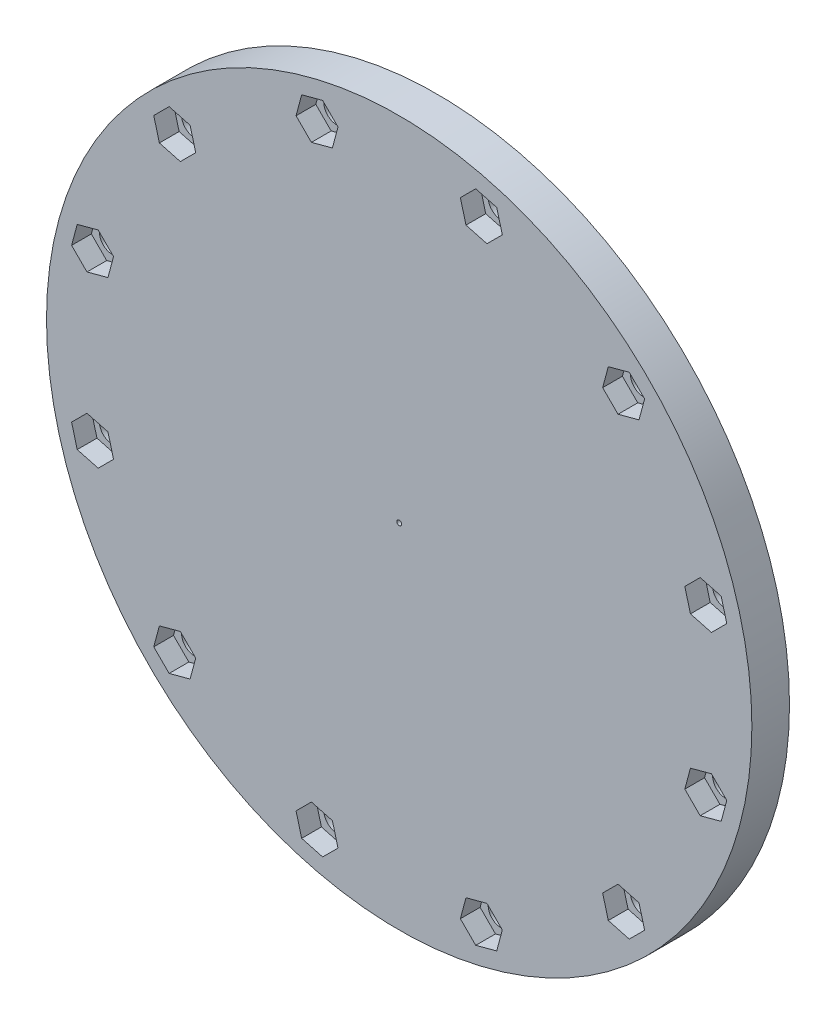
SolidWorks part; units mm, degrees
ref_plane "Front" through (0, 0, 0) normal (0, 0, 1) x (1, 0, 0)
ref_plane "Top" through (0, 0, 0) normal (0, 1, 0) x (1, 0, 0)
ref_plane "Right" through (0, 0, 0) normal (1, 0, 0) x (0, 0, -1)
sketch "Sketch1" plane through (0, 0, 0) normal (0, 0, 1) x (1, 0, 0)
  circle A0 centre (0, 0) radius 75
  dimension "D1" = 150
extrude "Boss-Extrude1" add sketch "Sketch1" along normal blind 8
hole_wizard "M5 Clearance Hole1" positions "Sketch3" profile "Sketch5" hole size "M5" standard "ANSI Metric" end condition up to next
sketch "Sketch3" plane through (0, 0, 0) normal (0, 0, -1) x (-1, 0, 0)
  line L14 (0, 0) -> (0, -75) construction
  line L15 (17.4703, -65.2) -> (-17.4703, 65.2) construction
  line L17 (65.2, 17.4703) -> (-65.2, -17.4703) construction
  line L19 (47.7297, 47.7297) -> (-47.7297, -47.7297) construction
  line L21 (0, 0) -> (17.4703, -65.2) construction
  line L23 (-17.4703, -65.2) -> (17.4703, 65.2) construction
  line L24 (-65.2, 17.4703) -> (65.2, -17.4703) construction
  line L26 (-47.7297, 47.7297) -> (47.7297, -47.7297) construction
  circle A1 centre (0, 0) radius 75 construction
  circle A3 centre (0, 0) radius 67.5 construction
  point P5 (-47.7297, 47.7297)
  point P11 (65.2, -17.4703)
  point P13 (47.7297, -47.7297)
  point P21 (-65.2, 17.4703)
  point P62 (-17.4703, 65.2)
  point P64 (-65.2, -17.4703)
  point P66 (-47.7297, -47.7297)
  point P68 (17.4703, -65.2)
  point P70 (17.4703, -65.2)
  point P72 (65.2, 17.4703)
  point P74 (47.7297, 47.7297)
  point P450 (17.4703, 65.2)
  point P453 (-17.4703, -65.2)
  dimension "D1" = 30
  dimension "D2" = 135
  dimension "D3" = 30
  dimension "D4" = 15
  dimension "D5" = 30
  dimension "D6" = 30
  dimension "D7" = 30
sketch "Sketch5" plane through (17.4703, -65.2, 0) normal (1, 0, 0) x (0, 1, 0)
  line L0 (0, 0) -> (0, 8)
  line L1 (0, 8) -> (2.75, 8)
  line L2 (2.75, 8) -> (2.75, 0)
  line L5 (2.75, 0) -> (0, 0)
  line L11 (0, -6.35) -> (0, 107.95) construction
  dimension "Thru Hole Dia." = 5.5
  dimension "Thru Hole Depth" = 8
sketch "Sketch6" plane through (0, 0, 8) normal (0, 0, -1) x (-1, 0, 0)
  line L0 (0, 0) -> (-47.7297, 47.7297) construction
  line L25 (-43.2683, 46.5343) -> (-44.4637, 50.9957)
  line L26 (-44.4637, 50.9957) -> (-48.9251, 52.1911)
  line L27 (-48.9251, 52.1911) -> (-52.1911, 48.9251)
  line L28 (-52.1911, 48.9251) -> (-50.9957, 44.4637)
  line L29 (-50.9957, 44.4637) -> (-46.5343, 43.2683)
  line L30 (-46.5343, 43.2683) -> (-43.2683, 46.5343)
  line L79 (-13.0089, 66.3954) -> (-16.2749, 69.6614)
  line L80 (-14.2043, 61.934) -> (-13.0089, 66.3954)
  line L81 (-18.6657, 60.7386) -> (-14.2043, 61.934)
  line L82 (-21.9317, 64.0046) -> (-18.6657, 60.7386)
  line L83 (-20.7363, 68.466) -> (-21.9317, 64.0046)
  line L84 (-16.2749, 69.6614) -> (-20.7363, 68.466)
  line L85 (21.9317, 64.0046) -> (20.7363, 68.466)
  line L86 (18.6657, 60.7386) -> (21.9317, 64.0046)
  line L87 (14.2043, 61.934) -> (18.6657, 60.7386)
  line L88 (13.0089, 66.3954) -> (14.2043, 61.934)
  line L89 (16.2749, 69.6614) -> (13.0089, 66.3954)
  line L90 (20.7363, 68.466) -> (16.2749, 69.6614)
  line L91 (50.9957, 44.4637) -> (52.1911, 48.9251)
  line L92 (46.5343, 43.2683) -> (50.9957, 44.4637)
  line L93 (43.2683, 46.5343) -> (46.5343, 43.2683)
  line L94 (44.4637, 50.9957) -> (43.2683, 46.5343)
  line L95 (48.9251, 52.1911) -> (44.4637, 50.9957)
  line L96 (52.1911, 48.9251) -> (48.9251, 52.1911)
  line L97 (66.3954, 13.0089) -> (69.6614, 16.2749)
  line L98 (61.934, 14.2043) -> (66.3954, 13.0089)
  line L99 (60.7386, 18.6657) -> (61.934, 14.2043)
  line L100 (64.0046, 21.9317) -> (60.7386, 18.6657)
  line L101 (68.466, 20.7363) -> (64.0046, 21.9317)
  line L102 (69.6614, 16.2749) -> (68.466, 20.7363)
  line L103 (64.0046, -21.9317) -> (68.466, -20.7363)
  line L104 (60.7386, -18.6657) -> (64.0046, -21.9317)
  line L105 (61.934, -14.2043) -> (60.7386, -18.6657)
  line L106 (66.3954, -13.0089) -> (61.934, -14.2043)
  line L107 (69.6614, -16.2749) -> (66.3954, -13.0089)
  line L108 (68.466, -20.7363) -> (69.6614, -16.2749)
  line L109 (44.4637, -50.9957) -> (48.9251, -52.1911)
  line L110 (43.2683, -46.5343) -> (44.4637, -50.9957)
  line L111 (46.5343, -43.2683) -> (43.2683, -46.5343)
  line L112 (50.9957, -44.4637) -> (46.5343, -43.2683)
  line L113 (52.1911, -48.9251) -> (50.9957, -44.4637)
  line L114 (48.9251, -52.1911) -> (52.1911, -48.9251)
  line L115 (13.0089, -66.3954) -> (16.2749, -69.6614)
  line L116 (14.2043, -61.934) -> (13.0089, -66.3954)
  line L117 (18.6657, -60.7386) -> (14.2043, -61.934)
  line L118 (21.9317, -64.0046) -> (18.6657, -60.7386)
  line L119 (20.7363, -68.466) -> (21.9317, -64.0046)
  line L120 (16.2749, -69.6614) -> (20.7363, -68.466)
  line L121 (-21.9317, -64.0046) -> (-20.7363, -68.466)
  line L122 (-18.6657, -60.7386) -> (-21.9317, -64.0046)
  line L123 (-14.2043, -61.934) -> (-18.6657, -60.7386)
  line L124 (-13.0089, -66.3954) -> (-14.2043, -61.934)
  line L125 (-16.2749, -69.6614) -> (-13.0089, -66.3954)
  line L126 (-20.7363, -68.466) -> (-16.2749, -69.6614)
  line L127 (-50.9957, -44.4637) -> (-52.1911, -48.9251)
  line L128 (-46.5343, -43.2683) -> (-50.9957, -44.4637)
  line L129 (-43.2683, -46.5343) -> (-46.5343, -43.2683)
  line L130 (-44.4637, -50.9957) -> (-43.2683, -46.5343)
  line L131 (-48.9251, -52.1911) -> (-44.4637, -50.9957)
  line L132 (-52.1911, -48.9251) -> (-48.9251, -52.1911)
  line L133 (-66.3954, -13.0089) -> (-69.6614, -16.2749)
  line L134 (-61.934, -14.2043) -> (-66.3954, -13.0089)
  line L135 (-60.7386, -18.6657) -> (-61.934, -14.2043)
  line L136 (-64.0046, -21.9317) -> (-60.7386, -18.6657)
  line L137 (-68.466, -20.7363) -> (-64.0046, -21.9317)
  line L138 (-69.6614, -16.2749) -> (-68.466, -20.7363)
  line L139 (-64.0046, 21.9317) -> (-68.466, 20.7363)
  line L140 (-60.7386, 18.6657) -> (-64.0046, 21.9317)
  line L141 (-61.934, 14.2043) -> (-60.7386, 18.6657)
  line L142 (-66.3954, 13.0089) -> (-61.934, 14.2043)
  line L143 (-69.6614, 16.2749) -> (-66.3954, 13.0089)
  line L144 (-68.466, 20.7363) -> (-69.6614, 16.2749)
  circle A6 centre (-47.7297, 47.7297) radius 4 construction
  circle A13 centre (-47.7297, 47.7297) radius 2.75 construction
  point P80 (0, 0)
  point P111 (-44.9013, 44.9013)
  dimension "D1" = 12
  dimension "D8" = 8
extrude "Cut-Extrude2" cut sketch "Sketch6" along normal blind 4.2
hole_wizard "Ø5.0mm Dowel Hole1" positions "Sketch8" profile "Sketch10" hole size "Ø5.0" standard "ANSI Metric"
sketch "Sketch8" plane through (0, 0, 0) normal (0, 0, -1) x (-1, 0, 0)
  circle A1 centre (0, 0) radius 67.5 construction
  point P545 (-30.1011, -60.4167)
  point P547 (-30.1011, 60.4167)
sketch "Sketch10" plane through (30.1011, 60.4167, 0) normal (1, 0, 0) x (0, 1, 0)
  line L0 (0, 0) -> (0, 6.4421)
  line L1 (0, 6.4421) -> (2.4, 5)
  line L2 (2.4, 5) -> (2.4, 0)
  line L5 (2.4, 0) -> (0, 0)
  line L10 (0, 6.4421) -> (-2.4, 5) construction
  line L11 (0, -6.35) -> (0, 107.95) construction
  dimension "Hole Dia." = 4.8
  dimension "Hole Depth" = 5
  dimension "Drill Angle" = 118
sketch "Sketch11" plane through (0, 0, 0) normal (0, 0, -1) x (-1, 0, 0)
  circle A0 centre (0, 0) radius 45.85
  dimension "D1" = 91.7
extrude "Cut-Extrude3" cut sketch "Sketch11" against normal blind 6
sketch "Sketch12" plane through (0, 0, 0) normal (0, 0, -1) x (-1, 0, 0)
  circle A0 centre (0, 0) radius 53.6575
  circle A1 centre (0, 0) radius 60.7695
  dimension "D1" = 107.315
  dimension "D2" = 7.112
extrude "Cut-Extrude4" cut sketch "Sketch12" against normal blind 4.1656
sketch "Sketch13" plane through (0, 0, 8) normal (0, 0, 1) x (1, 0, 0)
  line L0 (-17.4703, 65.2) -> (17.4703, -65.2) construction
  line L1 (65.2, 17.4703) -> (-65.2, -17.4703) construction
sketch "Sketch14" plane through (0, 0, 8) normal (0, 0, 1) x (1, 0, 0)
  circle A0 centre (0, 0) radius 0.5
  dimension "D1" = 1
extrude "center hole" cut sketch "Sketch14" against normal blind 1
